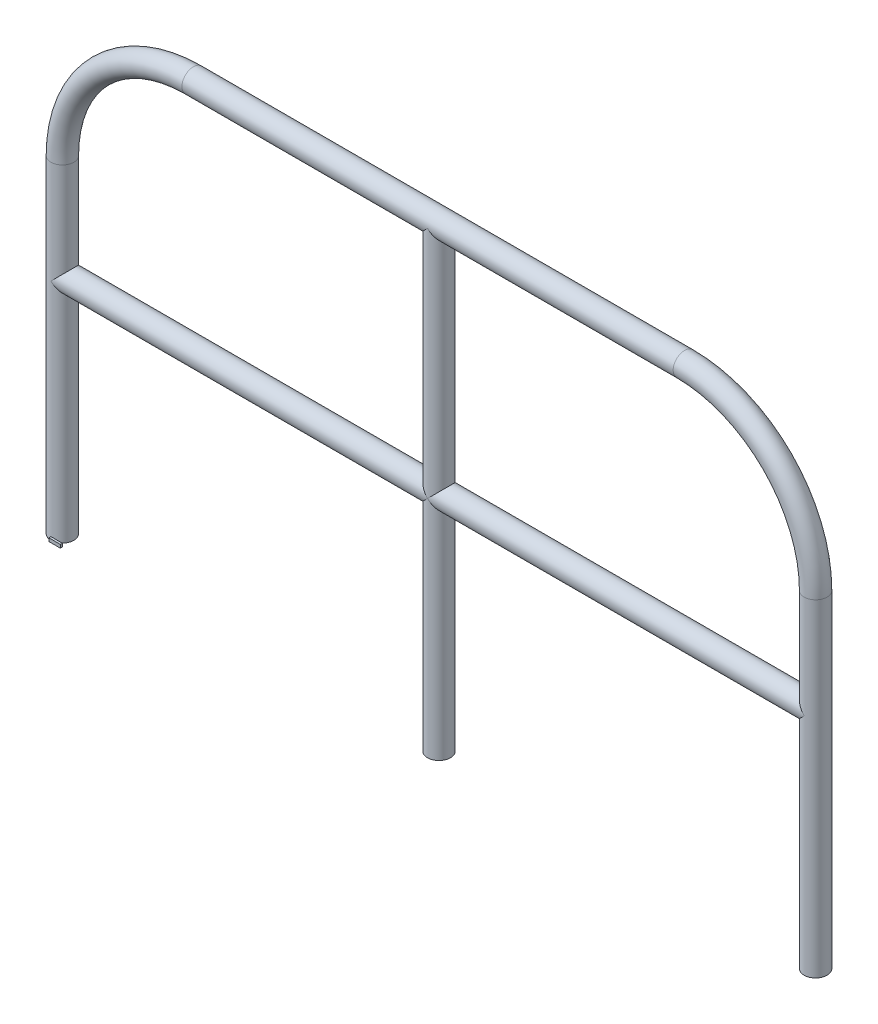
SolidWorks part; units mm, degrees
ref_plane "前视基准面" through (0, 0, 0) normal (0, 0, 1) x (1, 0, 0)
ref_plane "上视基准面" through (0, 0, 0) normal (0, 1, 0) x (1, 0, 0)
ref_plane "右视基准面" through (0, 0, 0) normal (1, 0, 0) x (0, 0, -1)
sketch "草图3" plane through (0, 0, 0) normal (0, 0, 1) x (1, 0, 0)
  line L0 (0, 0) -> (0, 1000)
  line L1 (400, 1400) -> (1900, 1400)
  line L2 (2300, 1000) -> (2300, 0)
  arc A0 (2300, 1000) -> (1900, 1400) centre (1900, 1000) ccw
  arc A1 (0, 1000) -> (400, 1400) centre (400, 1000) cw
  dimension "D1" = 400
  dimension "D2" = 1500
sketch "草图4" plane through (0, 0, 0) normal (0, 1, 0) x (1, 0, 0)
  circle A0 centre (0, 0) radius 35
  dimension "D1" = 70
sweep "扫描2" add profiles "草图4" path "草图3"
sketch "草图8" plane through (0, 0, 0) normal (0, -1, 0) x (1, 0, 0)
  line L0 (400, 0) -> (1900, 0) construction
  circle A0 centre (1150, 0) radius 35
extrude "凸台-拉伸6" add sketch "草图8" against normal blind 1400
sketch "草图9" plane through (0, 0, 0) normal (1, 0, 0) x (0, 0, -1)
  circle A0 centre (0, 685.7548) radius 35
extrude "凸台-拉伸7" add sketch "草图9" along normal blind 2300
sketch "草图10" plane through (0, 0, 0) normal (0, -1, 0) x (1, 0, 0)
  line L1 (0, 35) -> (35, 35)
  line L2 (0, 35) -> (0, 41.2225)
  line L3 (0, 41.2225) -> (35, 41.2225)
  line L4 (35, 35) -> (35, 41.2225)
  circle A0 centre (0, 0) radius 35 construction
  arc A1 (0, -35) -> (0, 35) centre (0, 0) ccw construction
extrude "凸台-拉伸8" add sketch "草图10" against normal blind 10 separate body
